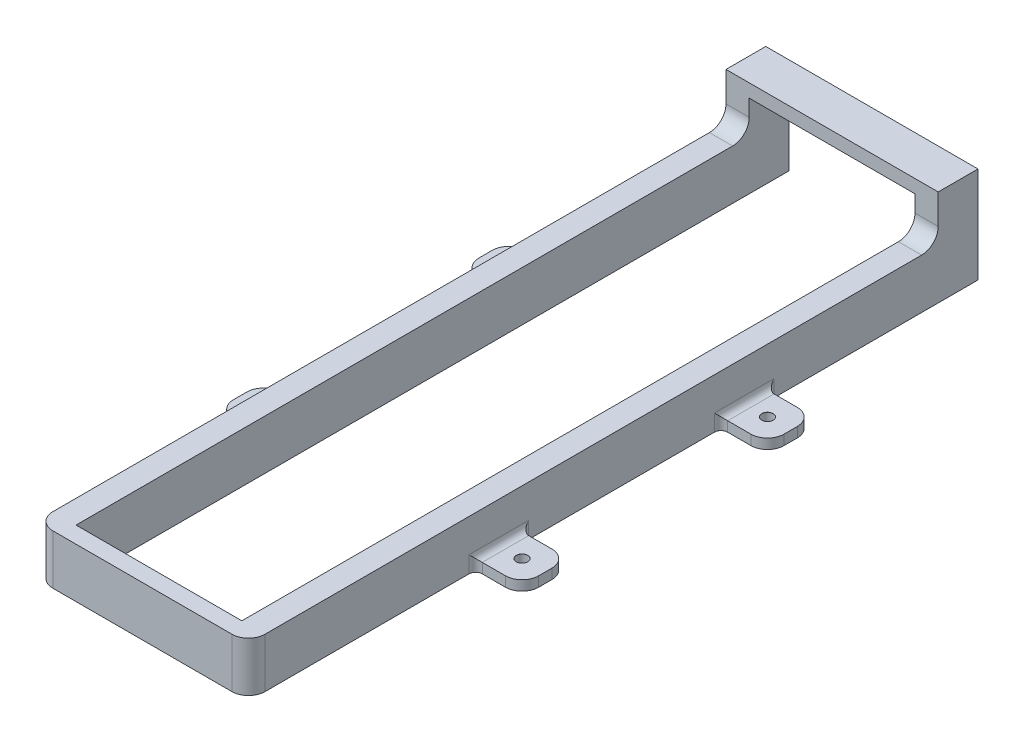
SolidWorks part; units mm, degrees
ref_plane "Front Plane" through (0, 0, 0) normal (0, 0, 1) x (1, 0, 0)
ref_plane "Top Plane" through (0, 0, 0) normal (0, 1, 0) x (1, 0, 0)
ref_plane "Right Plane" through (0, 0, 0) normal (1, 0, 0) x (0, 0, -1)
sketch "Sketch1" plane through (0, 0, 0) normal (0, 1, 0) x (1, 0, 0)
  line L0 (25, 107.5) -> (35, 107.5)
  line L2 (-25, 107.5) -> (-25, -107.5)
  line L3 (-25, -107.5) -> (25, -107.5)
  line L4 (25, 107.5) -> (25, -107.5)
  line L5 (-25, 107.5) -> (25, -107.5) construction
  line L6 (-25, -107.5) -> (25, 107.5) construction
  line L7 (35, 107.5) -> (35, -117.5)
  line L8 (35, -117.5) -> (-35, -117.5)
  line L9 (-35, -117.5) -> (-35, 107.5)
  line L10 (-35, 107.5) -> (-25, 107.5)
  point P0 (0, 0)
  dimension "D1" = 50
  dimension "D2" = 215
  dimension "D3" = 50
  dimension "D4" = 10
  dimension "D5" = 10
  dimension "D6" = 10
extrude "Boss-Extrude1" add sketch "Sketch1" along normal mid plane 15
sketch "Sketch2" plane through (0, 0, -107.5) normal (0, 0, -1) x (-1, 0, 0)
  line L1 (-35, 7.5) -> (-25, 7.5)
  line L2 (-35, 7.5) -> (-35, 17.5)
  line L3 (-35, 17.5) -> (-25, 17.5)
  line L4 (-25, 7.5) -> (-25, 17.5)
  line L5 (25, 7.5) -> (35, 7.5)
  line L6 (25, 7.5) -> (25, 17.5)
  line L7 (25, 17.5) -> (35, 17.5)
  line L8 (35, 7.5) -> (35, 17.5)
  line L9 (-35, 17.5) -> (35, 17.5)
  line L10 (-35, 17.5) -> (-35, 21.5)
  line L11 (-35, 21.5) -> (35, 21.5)
  line L12 (35, 17.5) -> (35, 21.5)
  line M7 (-25, 7.5) -> (-35, 7.5)
  dimension "D1" = 10
  dimension "D2" = 4
  dimension "D3" = 70
  dimension "D4" = 10
extrude "Boss-Extrude2" add sketch "Sketch2" against normal blind 12 contours L4 L3 L2 M7 | L7 L12 L11 L10 L3 L9 | L5 L8 L7 L6
sketch "Sketch3" plane through (0, 7.5, 0) normal (0, 1, 0) x (1, 0, 0)
  line L0 (35, -117.5) -> (35, 95.5) construction
  line L1 (-35, -117.5) -> (35, -117.5)
  line L2 (-35, -117.5) -> (-35, -112.5)
  line L3 (-32, -112.5) -> (32, -112.5)
  line L4 (35, -117.5) -> (35, -112.5)
  line L6 (-35, 107.5) -> (-32, 107.5)
  line L7 (-35, 107.5) -> (-35, -112.5)
  line L9 (-32, 107.5) -> (-32, -112.5)
  line L10 (35, 107.5) -> (32, 107.5)
  line L11 (35, 107.5) -> (35, -112.5)
  line L13 (32, 107.5) -> (32, -112.5)
  dimension "D1" = 5
  dimension "D2" = 3
  dimension "D3" = 3
extrude "Cut-Extrude1" cut sketch "Sketch3" against normal through all both and the other way through all
sketch "Sketch4" plane through (0, 7.5, 0) normal (0, 1, 0) x (1, 0, 0)
  line L0 (-32, -112.5) -> (-32, 95.5) construction
  line L1 (-32, 44) -> (-46, 44)
  line L2 (-32, 44) -> (-32, 30)
  line L3 (-32, 30) -> (-46, 30)
  line L4 (-46, 44) -> (-46, 30)
  line L10 (0, 0) -> (0, 40.3812) construction
  line L11 (46, -30) -> (46, -44)
  line L12 (-32, -30) -> (-46, -30)
  line L13 (-32, -30) -> (-32, -44)
  line L14 (-32, -44) -> (-46, -44)
  line L15 (-46, -30) -> (-46, -44)
  line L16 (32, -44) -> (46, -44)
  line L17 (32, -30) -> (32, -44)
  line L18 (32, -30) -> (46, -30)
  line L19 (46, 44) -> (46, 30)
  line L20 (32, 30) -> (46, 30)
  line L21 (32, 44) -> (32, 30)
  line L22 (32, 44) -> (46, 44)
  dimension "D1" = 14
  dimension "D2" = 14
  dimension "D3" = 14
  dimension "D4" = 14
  dimension "D5" = 30
  dimension "D6" = 30
extrude "Boss-Extrude3" add sketch "Sketch4" against normal up to surface (15 mm away) up to face at (0, -7.5, 1.25)
sketch "Sketch7" plane through (0, 7.5, 0) normal (0, 1, 0) x (1, 0, 0)
  line L1 (-46, 44) -> (-32, 44)
  line L2 (-46, 44) -> (-46, 30)
  line L3 (-46, 30) -> (-32, 30)
  line L4 (-32, 44) -> (-32, 30)
  line L5 (32, 44) -> (46, 44)
  line L6 (32, 44) -> (32, 30)
  line L7 (32, 30) -> (46, 30)
  line L8 (46, 44) -> (46, 30)
  line L9 (32, -30) -> (46, -30)
  line L10 (32, -30) -> (32, -44)
  line L11 (32, -44) -> (46, -44)
  line L12 (46, -30) -> (46, -44)
  line L13 (-46, -30) -> (-32, -30)
  line L14 (-46, -30) -> (-46, -44)
  line L15 (-46, -44) -> (-32, -44)
  line L16 (-32, -30) -> (-32, -44)
extrude "Cut-Extrude2" cut sketch "Sketch7" against normal blind 12
hole_wizard "M3 Clearance Hole1" positions "Sketch8" profile "Sketch9" hole size "M3" standard "ANSI Metric" end condition through all
sketch "Sketch8" plane through (0, -4.5, 0) normal (0, 1, 0) x (1, 0, 0)
  line L0 (-46, 44) -> (-46, 30) construction
  line L1 (-46, 30) -> (-32, 30) construction
  point P0 (-39, 37)
  point P2 (39, 37)
  point P4 (39, -37)
  point P6 (-39, -37)
  dimension "D1" = 7
  dimension "D2" = 85
  dimension "D3" = 7
  dimension "D4" = 67
sketch "Sketch9" plane through (-39, -4.5, -37) normal (1, 0, 0) x (0, 0, 1)
  line L0 (0, 0) -> (0, 3)
  line L1 (0, 3) -> (1.7, 3)
  line L2 (1.7, 3) -> (1.7, 0.025)
  line L3 (1.7, 0.025) -> (1.725, 0)
  line L5 (1.725, 0) -> (0, 0)
  line L6 (-1.7, 0.025) -> (-1.725, 0) construction
  line L11 (0, -6.35) -> (0, 107.95) construction
  dimension "Thru Hole Dia." = 3.4
  dimension "Thru Hole Depth" = 3
  dimension "Near C'Sink Dia." = 3.45
  dimension "Near C'Sink Angle" = 90
fillet "Fillet1" radius 2 12 edges at (-32, -6, -44) (-32, -4.5, -37) (-32, -6, -30) (-32, -6, 30) (-32, -4.5, 37) (-32, -6, 44) (32, -6, 44) (32, -4.5, 37) (32, -6, 30) (32, -6, -44) (32, -6, -30) (32, -4.5, -37)
fillet "Fillet2" radius 5 12 edges at (-46, -6, -30) (-46, -6, -44) (-46, -6, 30) (-46, -6, 44) (46, -6, -44) (46, -6, -30) (46, -6, 30) (46, -6, 44) (-32, 0, 112.5) (32, 0, 112.5) (-28.5, 7.5, -95.5) (28.5, 7.5, -95.5)
